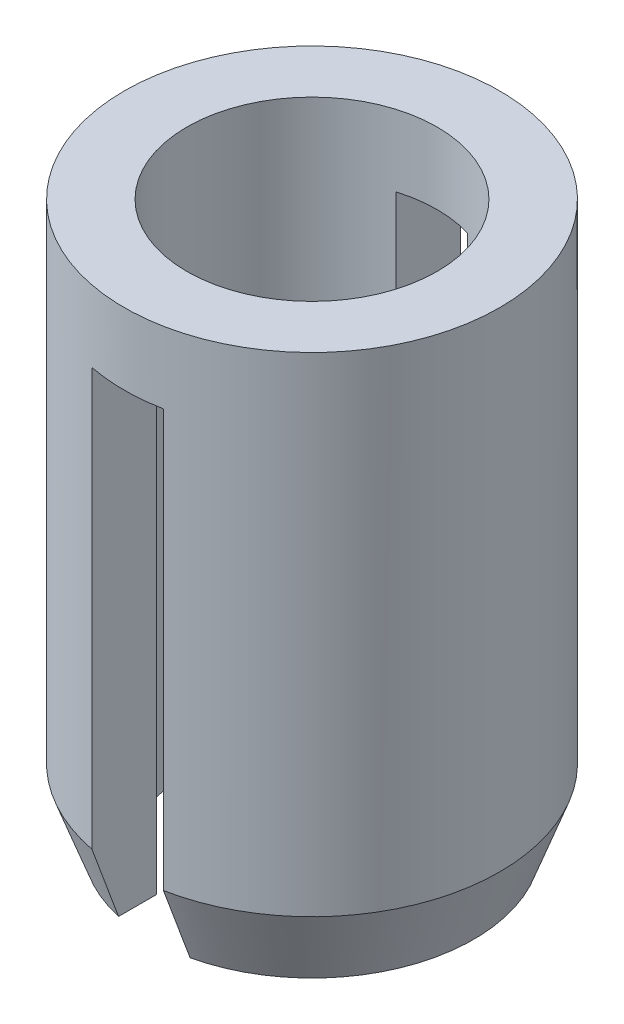
SolidWorks part; units mm, degrees
ref_plane "Front Plane" through (0, 0, 0) normal (0, 0, 1) x (1, 0, 0)
ref_plane "Top Plane" through (0, 0, 0) normal (0, 1, 0) x (1, 0, 0)
ref_plane "Right Plane" through (0, 0, 0) normal (1, 0, 0) x (0, 0, -1)
sketch "Sketch1" plane through (0, 0, 0) normal (0, 0, 1) x (1, 0, 0)
  line L0 (0, -9.4) -> (0, 0)
  line L1 (0, 0) -> (-3.15, 0)
  line L2 (-3.15, 0) -> (-3.15, -8.2)
  line L3 (-3.15, -8.2) -> (-2.7132, -9.4)
  line L4 (-2.7132, -9.4) -> (0, -9.4)
  line L5 (0, -9.4) -> (0, -6.7522) construction
  dimension "D1" = 9.4
  dimension "D2" = 6.3
  dimension "D3" = 1.2
  dimension "D4" = 20
revolve "Revolve1" add sketch "Sketch1" angle 360 about L5
hole_wizard "M5 Tapped Hole1" positions "Sketch3" profile "Sketch5" tap size "M5" standard "ISO" end condition through all
sketch "Sketch3" plane through (0, 0, 0) normal (0, 1, 0) x (1, 0, 0)
  point P0 (0, 0)
sketch "Sketch5" plane through (0, 0, 0) normal (1, 0, 0) x (0, 0, 1)
  line L0 (0, 0) -> (0, 9.4)
  line L1 (0, 9.4) -> (2.1, 9.4)
  line L2 (2.1, 9.4) -> (2.1, 0)
  line L5 (2.1, 0) -> (0, 0)
  line L11 (0, -6.35) -> (0, 107.95) construction
  dimension "Thru Tap Drill Dia." = 4.2
  dimension "Thru Tap Drill Depth" = 9.4
cosmetic thread "Hole Thread1" parameters "D2"=5
sketch "Sketch2" plane through (0, 0, 0) normal (0, 0, 1) x (1, 0, 0)
  line L0 (-2.1, -9.4) -> (2.1, -9.4) construction
  line L1 (0.6, -1.2) -> (-0.6, -1.2)
  line L2 (0.6, -1.2) -> (0.6, -9.4)
  line L3 (0.6, -9.4) -> (-0.6, -9.4)
  line L4 (-0.6, -1.2) -> (-0.6, -9.4)
  point P4 (0, -1.2)
  dimension "D1" = 1.2
  dimension "D2" = 1.2
extrude "Cut-Extrude1" cut sketch "Sketch2" against normal through all both and the other way through all
other "Freeze***"
